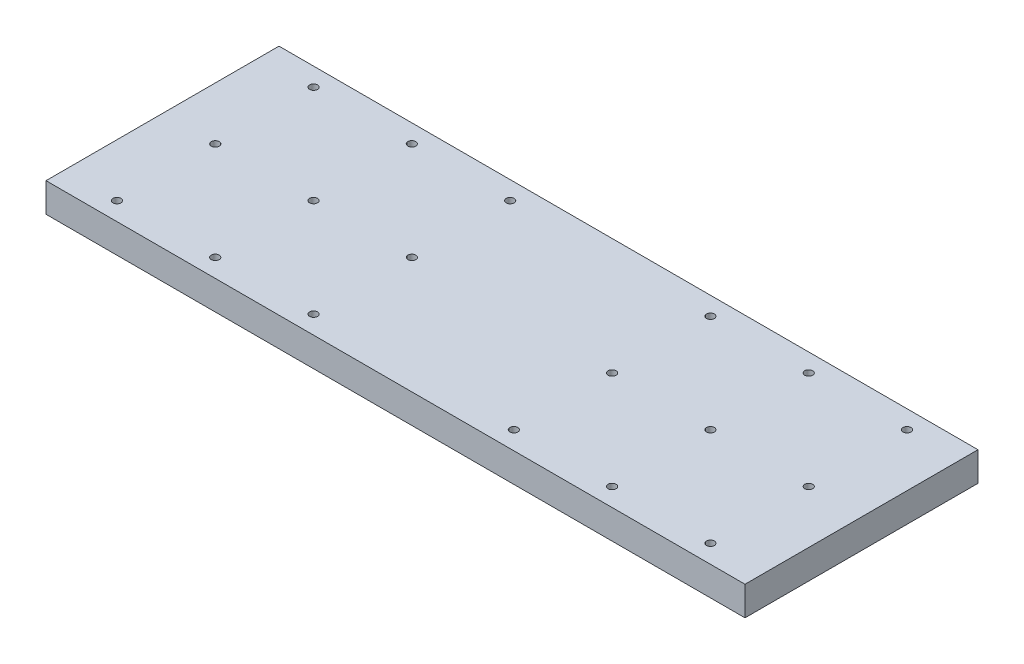
SolidWorks part; units mm, degrees
ref_plane "Front Plane" through (0, 0, 0) normal (0, 0, 1) x (1, 0, 0)
ref_plane "Top Plane" through (0, 0, 0) normal (0, 1, 0) x (1, 0, 0)
ref_plane "Right Plane" through (0, 0, 0) normal (1, 0, 0) x (0, 0, -1)
sketch "Sketch1" plane through (0, 0, 0) normal (0, 1, 0) x (1, 0, 0)
  line L1 (0, 0) -> (304.8, 0)
  line L2 (0, 0) -> (0, 101.6)
  line L3 (0, 101.6) -> (304.8, 101.6)
  line L4 (304.8, 0) -> (304.8, 101.6)
  dimension "D1" = 304.8
  dimension "D2" = 101.6
extrude "Boss-Extrude1" add sketch "Sketch1" along normal blind 12.7
sketch "Sketch2"
  line L0 (23.0188, 50.8) -> (281.7812, 50.8) construction
  line L1 (23.0188, 93.6625) -> (281.7812, 93.6625) construction
  line L2 (23.0188, 93.6625) -> (23.0188, 7.9375) construction
  line L3 (23.0188, 7.9375) -> (281.7812, 7.9375) construction
  line L4 (281.7812, 93.6625) -> (281.7812, 7.9375) construction
  line L5 (108.7438, 93.6625) -> (108.7438, 7.9375) construction
  line L6 (196.0562, 93.6625) -> (196.0562, 7.9375) construction
  line L7 (65.8572, 93.6625) -> (65.8572, 7.9375) construction
  line L8 (281.7812, 50.8) -> (304.8, 50.8) construction
  line L9 (304.8, 0) -> (304.8, 101.6) construction
  line L10 (238.9188, 93.6625) -> (238.9188, 7.9375) construction
  line L11 (23.0188, 50.8) -> (0, 50.8) construction
  line L12 (0, 101.6) -> (0, 0) construction
  line L13 (304.8, 101.6) -> (0, 101.6) construction
  point P22 (65.8572, 50.8)
  point P23 (238.9188, 50.8)
  point P24 (108.7438, 50.8)
  point P25 (196.0562, 50.8)
other "AlignGroup4" parameters "D1"=243.6364, "D2"=59.8351, "D3"=215.9, "D4"=85.725, "D5"=42.8384, "D6"=85.725, "D7"=159.747, "D8"=215.9, "D9"=258.7625, "D10"=85.725, "D11"=85.725, "D12"=258.7625, "D13"=85.725
other "AlignGroup5"
hole_wizard "#8-32 Tapped Hole1" positions "Sketch4" profile "Sketch3" tap size "#8-32" standard "ANSI Inch" end condition through all
sketch "Sketch4" plane through (0, 12.7, 0) normal (0, 1, 0) x (1, 0, 0)
  line L0 (108.7438, 93.6625) -> (108.7438, 7.9375) construction
  point P0 (23.0188, 93.6625)
  point P3 (65.8572, 93.6625)
  point P6 (108.7438, 93.6625)
  point P9 (196.0562, 93.6625)
  point P12 (238.9188, 93.6625)
  point P15 (281.7812, 93.6625)
  point P18 (23.0188, 50.8)
  point P21 (65.8572, 50.8)
  point P24 (108.7438, 50.8)
  point P28 (196.0562, 50.8)
  point P31 (238.9188, 50.8)
  point P34 (281.7812, 50.8)
  point P37 (23.0188, 7.9375)
  point P40 (65.8572, 7.9375)
  point P43 (108.7438, 7.9375)
  point P46 (196.0562, 7.9375)
  point P49 (238.9188, 7.9375)
  point P52 (281.7812, 7.9375)
sketch "Sketch3" plane through (23.0188, 12.7, -93.6625) normal (1, 0, 0) x (0, 0, 1)
  line L0 (0, 0) -> (0, 12.7)
  line L1 (0, 12.7) -> (1.7272, 12.7)
  line L2 (1.7272, 12.7) -> (1.7272, 0)
  line L5 (1.7272, 0) -> (0, 0)
  line L11 (0, -6.35) -> (0, 107.95) construction
  dimension "Thru Tap Drill Dia." = 3.4544
  dimension "Thru Tap Drill Depth" = 12.7
cosmetic thread "Hole Thread1"
cosmetic thread "Hole Thread2"
cosmetic thread "Hole Thread3"
cosmetic thread "Hole Thread4"
cosmetic thread "Hole Thread5"
cosmetic thread "Hole Thread6"
cosmetic thread "Hole Thread7"
cosmetic thread "Hole Thread8"
cosmetic thread "Hole Thread9"
cosmetic thread "Hole Thread10"
cosmetic thread "Hole Thread11"
cosmetic thread "Hole Thread12"
cosmetic thread "Hole Thread13"
cosmetic thread "Hole Thread14"
cosmetic thread "Hole Thread15"
cosmetic thread "Hole Thread16"
cosmetic thread "Hole Thread17"
cosmetic thread "Hole Thread18"
